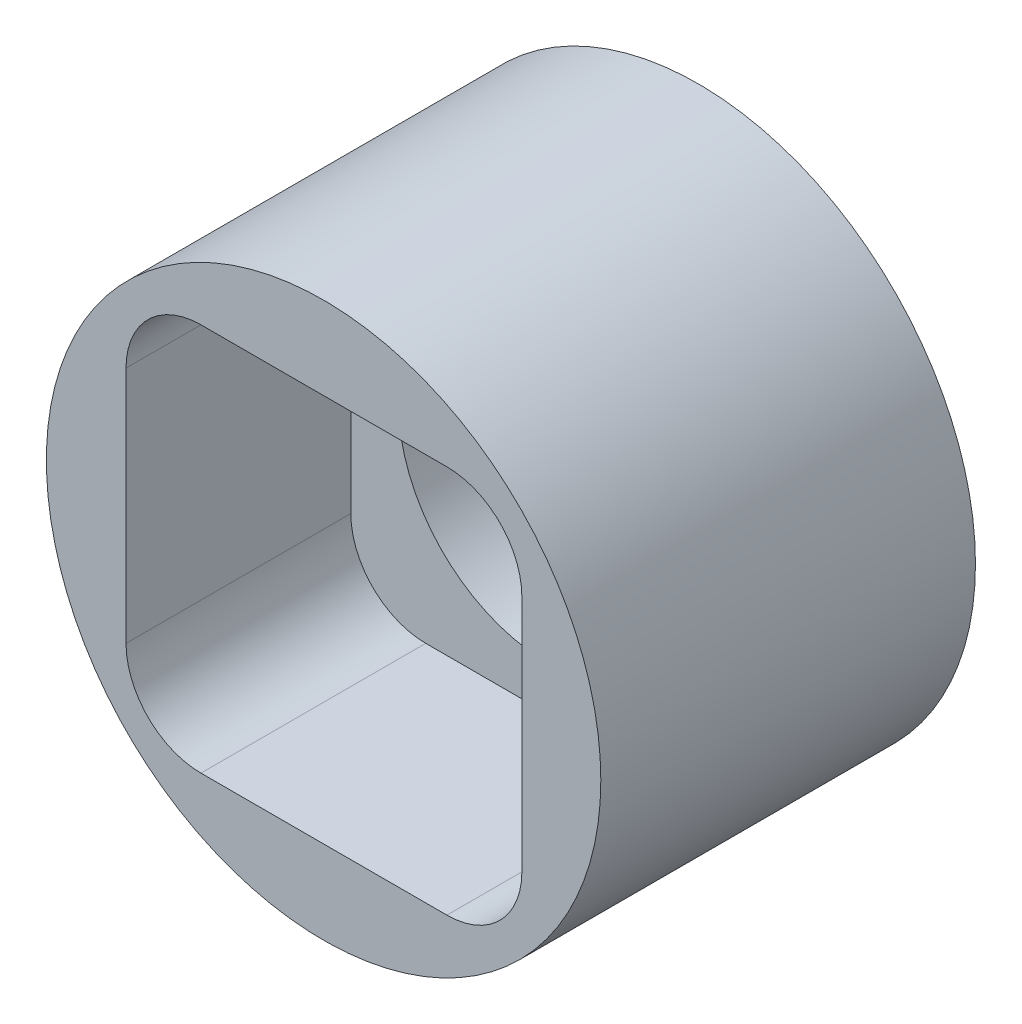
SolidWorks part; units mm, degrees
ref_plane "前视基准面" through (0, 0, 0) normal (0, 0, 1) x (1, 0, 0)
ref_plane "上视基准面" through (0, 0, 0) normal (0, 1, 0) x (1, 0, 0)
ref_plane "右视基准面" through (0, 0, 0) normal (1, 0, 0) x (0, 0, -1)
other "Configuration Table"
sketch "草图1" plane through (0, 0, 0) normal (0, 0, 1) x (1, 0, 0)
  circle A0 centre (0, 0) radius 3.7
extrude "凸台-拉伸1" add sketch "草图1" along normal blind 5
sketch "草图2" plane through (0, 0, 5) normal (0, 0, 1) x (1, 0, 0)
  line L1 (-1.6369, 2.5956) -> (1.6462, 2.5956)
  line L2 (-2.6369, 1.5956) -> (-2.6369, -1.5861)
  line L3 (-1.6369, -2.5861) -> (1.6462, -2.5861)
  line L4 (2.6462, 1.5956) -> (2.6462, -1.5861)
  arc A1 (1.6462, -2.5861) -> (2.6462, -1.5861) centre (1.6462, -1.5861) ccw
  arc A2 (1.6462, 2.5956) -> (2.6462, 1.5956) centre (1.6462, 1.5956) cw
  arc A3 (-2.6369, -1.5861) -> (-1.6369, -2.5861) centre (-1.6369, -1.5861) ccw
  arc A4 (-1.6369, 2.5956) -> (-2.6369, 1.5956) centre (-1.6369, 1.5956) ccw
extrude "切除-拉伸1" cut sketch "草图2" against normal blind 3
sketch "草图3" plane through (0, 0, 2) normal (0, 0, 1) x (1, 0, 0)
  circle A0 centre (0, 0) radius 2
extrude "切除-拉伸2" cut sketch "草图3" against normal blind 2
